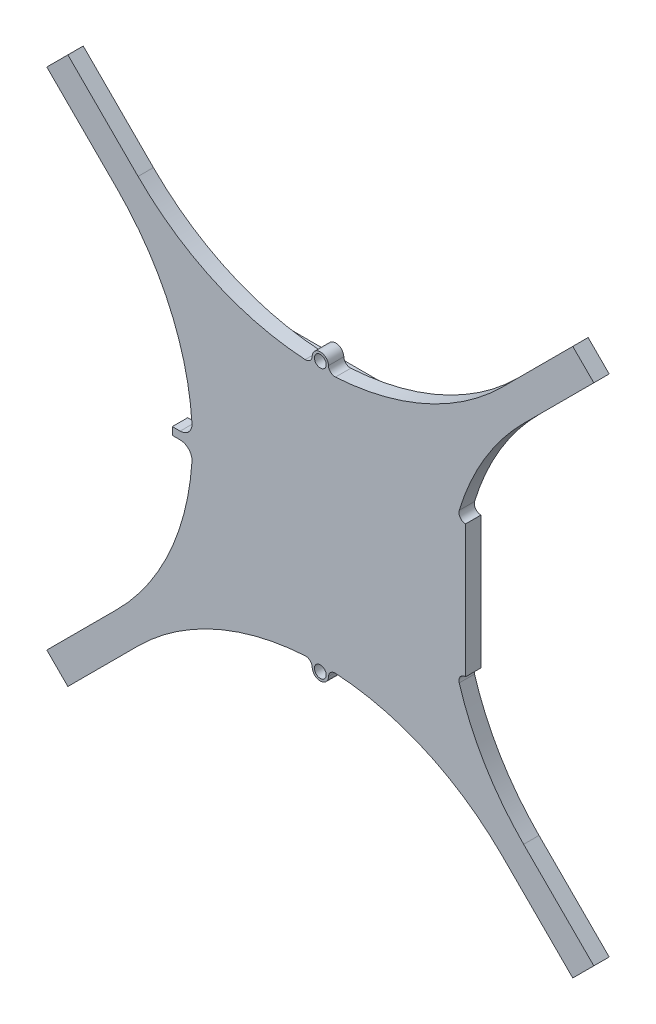
SolidWorks part; units mm, degrees
material "ABS"
ref_plane "Front Plane" through (0, 0, 0) normal (0, 0, 1) x (1, 0, 0)
ref_plane "Top Plane" through (0, 0, 0) normal (0, 1, 0) x (1, 0, 0)
ref_plane "Right Plane" through (0, 0, 0) normal (1, 0, 0) x (0, 0, -1)
other "Center of Mass"
sketch "Sketch1" plane through (0, 0, 0) normal (0, 0, 1) x (1, 0, 0)
  line L0 (-27.1352, 29.398) -> (-29.398, 27.1352)
  line L1 (-21.8551, 19.5923) -> (-29.398, 27.1352)
  line L2 (-21.8551, -19.5923) -> (-29.398, -27.1352)
  line L3 (29.398, 27.1352) -> (27.1352, 29.398)
  line L4 (0, 0) -> (0, -41.4474) construction
  line L5 (19.5923, 21.8551) -> (27.1352, 29.398)
  line L6 (-19.5923, 21.8551) -> (-27.1352, 29.398)
  line L7 (27.1352, -29.398) -> (29.398, -27.1352)
  line L8 (21.8551, -19.5923) -> (29.398, -27.1352)
  line L9 (21.8551, 19.5923) -> (29.398, 27.1352)
  line L10 (19.5923, -21.8551) -> (27.1352, -29.398)
  line L11 (0, 0) -> (0, 41.4474) construction
  line L12 (-29.398, -27.1352) -> (-27.1352, -29.398)
  line L13 (0, 0) -> (-15.9085, 0) construction
  line L14 (15.6189, 7.115) -> (15.6189, -7.115)
  line L15 (0, 0) -> (33.3791, 33.3791) construction
  line L16 (15.6189, 7.115) -> (14.6688, 7.115)
  line L17 (-19.5923, -21.8551) -> (-27.1352, -29.398)
  line L18 (15.6189, -7.115) -> (14.6688, -7.115)
  line L19 (-15.9085, -0.4114) -> (-13.7427, -0.4114)
  line L20 (-15.9085, -0.4114) -> (-15.9085, 0.4114)
  line L21 (-15.9085, 0.4114) -> (-13.7427, 0.4114)
  arc A0 (19.5923, -21.8551) -> (0.5189, -13.7445) centre (0, -41.4474) ccw
  arc A1 (-21.8551, -19.5923) -> (-13.7427, -0.4114) centre (-41.4474, 0) ccw
  arc A2 (-19.5923, 21.8551) -> (-0.5189, 13.7445) centre (0, 41.4474) ccw
  arc A3 (21.8551, 19.5923) -> (14.6688, 7.115) centre (41.4474, 0) ccw
  arc A4 (0.5189, 13.7445) -> (-0.5189, 13.7445) centre (0, 14.4491) ccw
  circle A5 centre (0, 14.4491) radius 0.6348
  arc A6 (0.5189, 13.7445) -> (19.5923, 21.8551) centre (0, 41.4474) ccw
  circle A7 centre (0, -14.4491) radius 0.6348
  arc A8 (0.5189, -13.7445) -> (-0.5189, -13.7445) centre (0, -14.4491) cw
  arc A9 (-0.5189, -13.7445) -> (-19.5923, -21.8551) centre (0, -41.4474) ccw
  arc A10 (14.6688, -7.115) -> (21.8551, -19.5923) centre (41.4474, 0) ccw
  arc A11 (-13.7427, 0.4114) -> (-21.8551, 19.5923) centre (-41.4474, 0) ccw
  point P17 (0, 0)
  point P32 (0, 0)
  point P33 (0, 0)
  point P39 (15.6189, 0)
  dimension "D2" = 27.7077
  dimension "D10" = 1.75
  dimension "D11" = 14.4491
  dimension "D12" = 0.2402
  dimension "D1" = 41.4474
  dimension "D3" = 4
  dimension "D4" = 135
  dimension "D5" = 4
  dimension "D6" = 10.6673
  dimension "D7" = 3.2
  dimension "D8" = 39.975
  dimension "D13" = 15.6189
  dimension "D14" = 7.115
  dimension "D15" = 0.4114
  dimension "D16" = 2.1658
  dimension "D9" = 4
extrude "Boss-Extrude1" add sketch "Sketch1" along normal blind 1.65
fillet "Fillet1" radius 0.7112 4 edges at (-0.5189, -13.7445, 0.825) (0.5189, -13.7445, 0.825) (-0.5189, 13.7445, 0.825) (0.5189, 13.7445, 0.825)
fillet "Fillet2" radius 0.7112 2 edges at (14.6688, -7.115, 0.825) (14.6688, 7.115, 0.825)
fillet "Fillet3" radius 1.27 2 edges at (-13.7427, 0.4114, 0.825) (-13.7427, -0.4114, 0.825)
sketch "Sketch2" plane through (0, 0, 0) normal (0, 0, -1) x (-1, 0, 0)
  line L0 (0, 14.4491) -> (0, -14.4491) construction
  line L1 (15.9085, 0) -> (-15.6189, 0) construction
  line L2 (11.5, 9.228) -> (-11.5, 9.228)
  line L3 (11.5, 9.228) -> (11.5, -9.228) construction
  line L4 (11.5, -9.228) -> (-11.5, -9.228)
  line L5 (-11.5, 9.228) -> (-11.5, -9.228) construction
  line L6 (15.9085, 0.4114) -> (15.9085, -0.4114) construction
  line L7 (-15.6189, -7.115) -> (-15.6189, 7.115) construction
  line L8 (11.5, -9.228) -> (11.5, -11.542)
  line L9 (11.5, -11.542) -> (-11.5, -11.542)
  line L10 (-11.5, -11.542) -> (-11.5, -9.228)
  line L11 (-11.5, 11.542) -> (-11.5, 9.228)
  line L12 (11.5, 11.542) -> (-11.5, 11.542)
  line L13 (11.5, 9.228) -> (11.5, 11.542)
  line L14 (11.5, -10.385) -> (-11.5, -10.385) construction
  circle A0 centre (8, -10.385) radius 0.33
  circle A1 centre (6.222, -10.385) radius 0.33
  circle A2 centre (4.444, -10.385) radius 0.33
  circle A3 centre (2.666, -10.385) radius 0.33
  circle A4 centre (0.888, -10.385) radius 0.33
  circle A5 centre (-0.89, -10.385) radius 0.33
  circle A6 centre (-2.668, -10.385) radius 0.33
  circle A7 centre (-4.446, -10.385) radius 0.33
  circle A8 centre (-6.224, -10.385) radius 0.33
  circle A9 centre (-8.002, -10.385) radius 0.33
  circle A10 centre (-8.002, 10.385) radius 0.33
  circle A11 centre (-6.224, 10.385) radius 0.33
  circle A12 centre (-4.446, 10.385) radius 0.33
  circle A13 centre (-2.668, 10.385) radius 0.33
  circle A14 centre (-0.89, 10.385) radius 0.33
  circle A15 centre (0.888, 10.385) radius 0.33
  circle A16 centre (2.666, 10.385) radius 0.33
  circle A17 centre (4.444, 10.385) radius 0.33
  circle A18 centre (6.222, 10.385) radius 0.33
  circle A19 centre (8, 10.385) radius 0.33
  point P8 (0, 9.228)
  point P15 (11.5, 0)
  dimension "D4" = 0.66
  dimension "D1" = 18.456
  dimension "D2" = 23
  dimension "D3" = 2.314
  dimension "D5" = 3.5
  dimension "D6" = 10
extrude "Boss-Extrude2" add sketch "Sketch2" along normal blind 2.6
